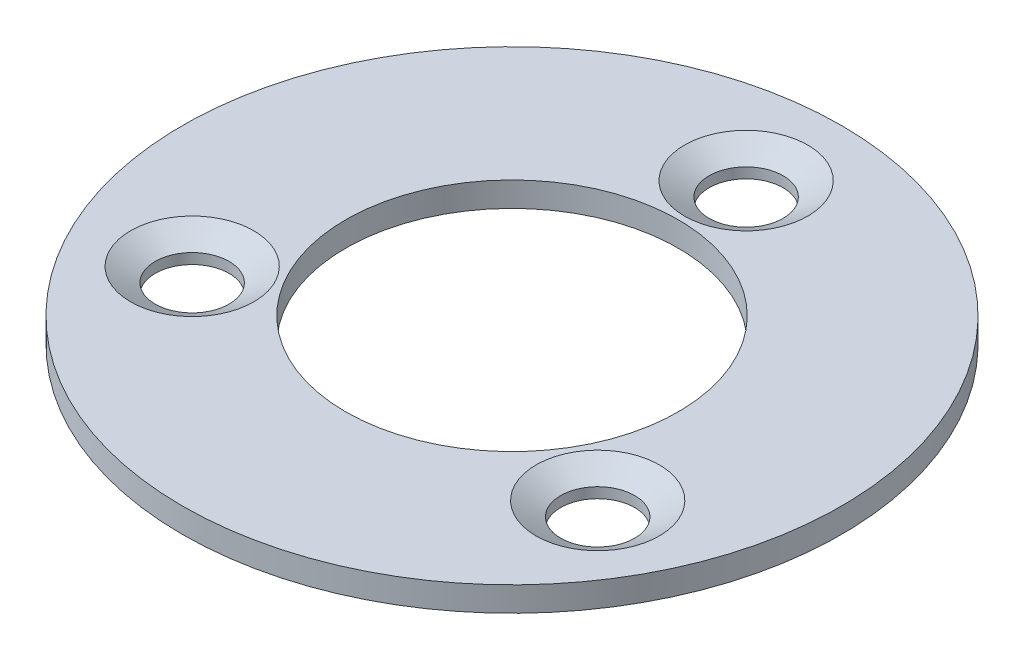
SolidWorks part; units mm, degrees
material "A-玻璃纤维"
ref_plane "前视基准面" through (0, 0, 0) normal (0, 0, 1) x (1, 0, 0)
ref_plane "上视基准面" through (0, 0, 0) normal (0, 1, 0) x (1, 0, 0)
ref_plane "右视基准面" through (0, 0, 0) normal (1, 0, 0) x (0, 0, -1)
sketch "草图1" plane through (0, 0, 0) normal (0, 1, 0) x (1, 0, 0)
  circle A0 centre (0, 0) radius 6.75
  circle A1 centre (0, 0) radius 13.3718
  dimension "D1" = 13.5
extrude "凸台-拉伸1" add sketch "草图1" along normal blind 1
sketch "草图2" plane through (0, 1, 0) normal (0, 1, 0) x (1, 0, 0)
  line L0 (-15.456, 0) -> (17.23, 0) construction
  line L1 (0, 14.3992) -> (0, -14.9276) construction
  line L2 (0, 0) -> (-15.046, -8.6868) construction
  line L3 (0, 0) -> (15.046, -8.6868) construction
  circle A0 centre (0, 9.5) radius 1.5
  circle A1 centre (8.2272, -4.75) radius 1.5
  circle A2 centre (-8.2272, -4.75) radius 1.5
  dimension "D2" = 3
  dimension "D3" = 9.5
  dimension "D1" = 60
  dimension "D4" = 3
extrude "切除-拉伸1" cut sketch "草图2" against normal blind 2
chamfer "倒角1" distance 1 angle 30 3 edges at (8.2272, 1, 6.25) (-8.2272, 1, 6.25) (0, 1, -8)
